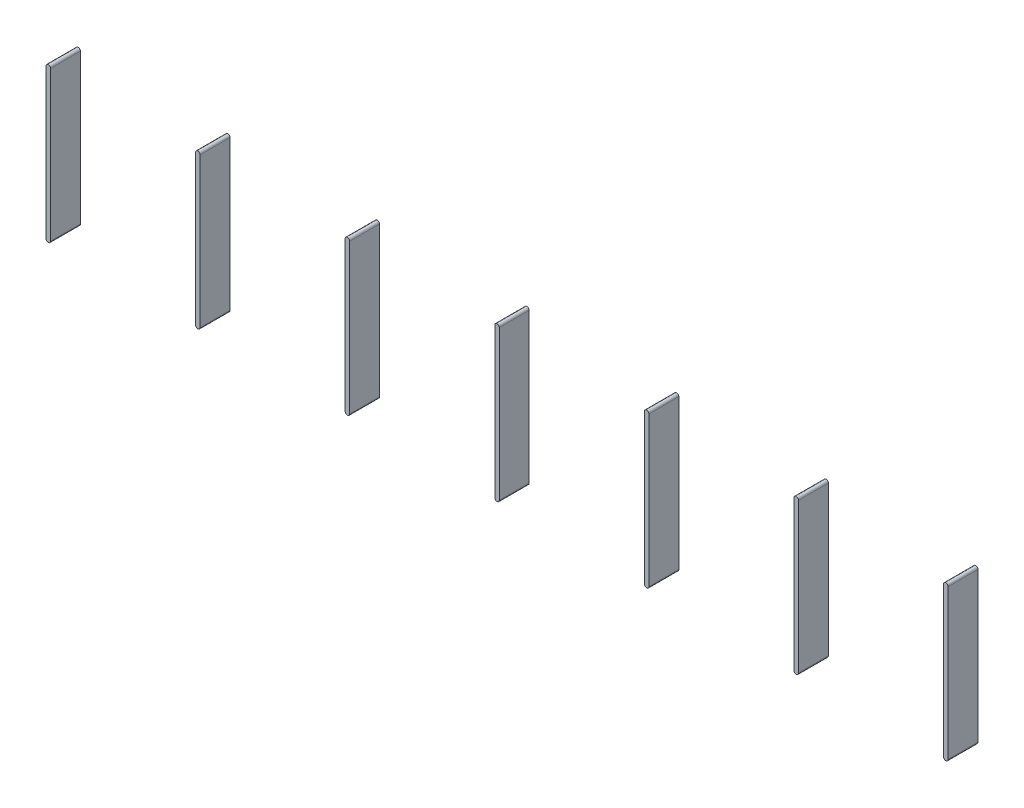
SolidWorks part; units mm, degrees
ref_plane "Front Plane" through (0, 0, 0) normal (0, 0, 1) x (1, 0, 0)
ref_plane "Top Plane" through (0, 0, 0) normal (0, 1, 0) x (1, 0, 0)
ref_plane "Right Plane" through (0, 0, 0) normal (1, 0, 0) x (0, 0, -1)
sketch "Sketch1" plane through (0, 0, 0) normal (0, 0, 1) x (1, 0, 0)
  line L0 (0, 0) -> (0, -20) construction
  line L1 (0.3, 0) -> (0.3, -20)
  line L2 (-0.3, 0) -> (-0.3, -20)
  line L3 (40, 0) -> (40, -20) construction
  line L4 (40.3, 0) -> (40.3, -20)
  line L5 (39.7, 0) -> (39.7, -20)
  line L6 (20, 0) -> (20, -20) construction
  line L7 (20.3, 0) -> (20.3, -20)
  line L8 (19.7, 0) -> (19.7, -20)
  line L9 (-20, 0) -> (-20, -20) construction
  line L10 (-19.7, 0) -> (-19.7, -20)
  line L11 (-20.3, 0) -> (-20.3, -20)
  line L12 (-40, 0) -> (-40, -20) construction
  line L13 (-39.7, 0) -> (-39.7, -20)
  line L14 (-40.3, 0) -> (-40.3, -20)
  line L15 (-60, 0) -> (-60, -20) construction
  line L16 (-59.7, 0) -> (-59.7, -20)
  line L17 (-60.3, 0) -> (-60.3, -20)
  line L18 (-80, 0) -> (-80, -20) construction
  line L19 (-79.7, 0) -> (-79.7, -20)
  line L20 (-80.3, 0) -> (-80.3, -20)
  line L21 (-80, -20) -> (-60, -20) construction
  line L22 (-60, -20) -> (-40, -20) construction
  line L23 (-40, -20) -> (-20, -20) construction
  line L24 (-20, -20) -> (0, -20) construction
  line L25 (0, -20) -> (20, -20) construction
  line L26 (20, -20) -> (40, -20) construction
  arc A0 (0.3, 0) -> (-0.3, 0) centre (0, 0) ccw
  arc A1 (-0.3, -20) -> (0.3, -20) centre (0, -20) ccw
  arc A2 (40.3, 0) -> (39.7, 0) centre (40, 0) ccw
  arc A3 (39.7, -20) -> (40.3, -20) centre (40, -20) ccw
  arc A4 (20.3, 0) -> (19.7, 0) centre (20, 0) ccw
  arc A5 (19.7, -20) -> (20.3, -20) centre (20, -20) ccw
  arc A6 (-19.7, 0) -> (-20.3, 0) centre (-20, 0) ccw
  arc A7 (-20.3, -20) -> (-19.7, -20) centre (-20, -20) ccw
  arc A8 (-39.7, 0) -> (-40.3, 0) centre (-40, 0) ccw
  arc A9 (-40.3, -20) -> (-39.7, -20) centre (-40, -20) ccw
  arc A10 (-59.7, 0) -> (-60.3, 0) centre (-60, 0) ccw
  arc A11 (-60.3, -20) -> (-59.7, -20) centre (-60, -20) ccw
  arc A12 (-79.7, 0) -> (-80.3, 0) centre (-80, 0) ccw
  arc A13 (-80.3, -20) -> (-79.7, -20) centre (-80, -20) ccw
  point P3 (0, -10)
  point P10 (40, -10)
  point P17 (20, -10)
  point P24 (-20, -10)
  point P31 (-40, -10)
  point P38 (-60, -10)
  point P45 (-80, -10)
  dimension "D1" = 0.3
  dimension "D2" = 20
  dimension "D3" = 20
extrude "Boss-Extrude1" add sketch "Sketch1" along normal blind 4
